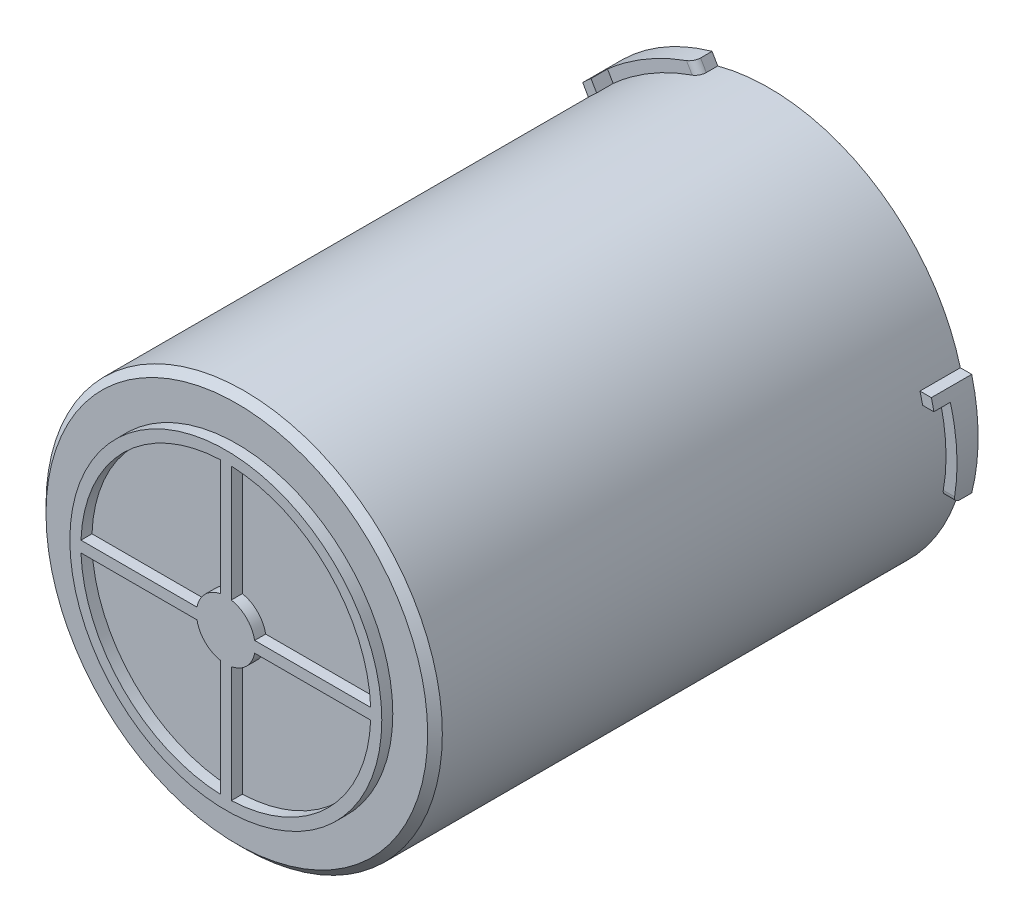
SolidWorks part; units mm, degrees
ref_plane "Спереди" through (0, 0, 0) normal (0, 0, 1) x (1, 0, 0)
ref_plane "Сверху" through (0, 0, 0) normal (0, 1, 0) x (1, 0, 0)
ref_plane "Справа" through (0, 0, 0) normal (1, 0, 0) x (0, 0, -1)
other "Configuration Table"
sketch "Эскиз1" plane through (0, 0, 0) normal (0, 1, 0) x (1, 0, 0)
  line L6 (0, 0) -> (-54, 0)
  line L7 (-54, 0) -> (-54, 145)
  line L8 (-54, 145) -> (-51, 145)
  line L9 (-51, 145) -> (-51, 3)
  line L10 (-51, 3) -> (0, 3)
  line L11 (0, 3) -> (0, 0)
  dimension "D1" = 3
  dimension "D2" = 3
  dimension "D3" = 145
  dimension "D4" = 54
revolve "Повернуть1" add sketch "Эскиз1" angle 360 about L11
ref_plane "Плоскость2" through (57, 0, 0) normal (1, 0, 0) x (0, 0, -1)
sketch "Эскиз2" plane through (57, 0, 0) normal (1, 0, 0) x (0, 0, -1)
  line L0 (145, 14) -> (145, -14)
  line L1 (145, -54) -> (145, 54) construction
  line L2 (145, -14) -> (140, -14)
  line L3 (140, -14) -> (138.5, 11)
  line L4 (138.5, 11) -> (134, 11)
  line L5 (134, 11) -> (134, 14)
  line L6 (134, 14) -> (145, 14)
  point P8 (0, 0)
  dimension "D1" = 28
  dimension "D2" = 3
  dimension "D3" = 6.5
  dimension "D4" = 11
  dimension "D5" = 5
  dimension "D6" = 14
extrude "Бобышка-Вытянуть1" add sketch "Эскиз2" against normal blind 10
fillet "Скругление1" radius 2 1 edges at (54.5768, -14, -140)
pattern_circular "Круговой массив2" count 3 over 360 about axis through (0, 0, 0) along (0, 0, 1) of "Бобышка-Вытянуть1", "Скругление1"
sketch "Эскиз3" plane through (0, 0, -145) normal (0, 0, -1) x (-1, 0, 0)
  circle A0 centre (0, 0) radius 51
extrude "Вырез-Вытянуть1" cut sketch "Эскиз3" against normal blind 15
sketch "Эскиз4" plane through (0, 0, -145) normal (0, 0, -1) x (-1, 0, 0)
  circle A0 centre (0, 0) radius 57
  circle A1 centre (0, 0) radius 62.6187
extrude "Вырез-Вытянуть2" cut sketch "Эскиз4" against normal blind 15
chamfer "Фаска1" distance 2 angle 45 1 edges at (-54, 0, 0)
sketch "Эскиз5" plane through (0, 0, 0) normal (0, 0, 1) x (1, 0, 0)
  circle A0 centre (0, 0) radius 42.5
  dimension "D1" = 85
fillet "Скругление2" radius 5 1 edges at (-51, 0, -3)
extrude "Бобышка-Вытянуть2" add sketch "Эскиз5" along normal blind 3
sketch "Эскиз7" plane through (0, 0, 3) normal (0, 0, 1) x (1, 0, 0)
  circle A0 centre (0, 0) radius 39.5
  dimension "D1" = 79
extrude "Вырез-Вытянуть3" cut sketch "Эскиз7" against normal up to surface (3 mm away) up to face at (42.5, 0, 0)
sketch "Эскиз8" plane through (0, 0, 0) normal (0, 0, 1) x (1, 0, 0)
  line L0 (-1.5, -41) -> (-1.5, 41)
  line L1 (-1.5, -41) -> (1.5, -41)
  line L2 (-1.5, 41) -> (1.5, 41)
  line L3 (1.5, -41) -> (1.5, 41)
  line L4 (-1.5, -41) -> (1.5, 41) construction
  line L5 (-1.5, 41) -> (1.5, -41) construction
  line L6 (-41, -1.5) -> (41, -1.5)
  line L7 (-41, -1.5) -> (-41, 1.5)
  line L8 (41, -1.5) -> (41, 1.5)
  line L9 (-41, 1.5) -> (41, 1.5)
  line L10 (-41, -1.5) -> (41, 1.5) construction
  line L11 (41, -1.5) -> (-41, 1.5) construction
  circle A0 centre (0, 0) radius 8
  circle M1 centre (0, 0) radius 39.5
  dimension "D1" = 16
  dimension "D2" = 3
  dimension "D3" = 82
  dimension "D4" = 82
  dimension "D5" = 3
extrude "Бобышка-Вытянуть4" add sketch "Эскиз8" along normal blind 3 contours A0 L3 L0 M1 | L3 A0 L0 L9 | L9 A0 L3 | L6 A0 L9 L3 | A0 L6 L9 M1 | L3 A0 L6 | L0 A0 L3 L6 | L9 L0 L6 L3 | L0 A0 L9 | L9 A0 L6 L0 | A0 L9 L6 M1 | L6 A0 L0 | A0 L0 L3 M1
equation "\"d\"=3"
equation "\"D1@Эскиз1\"=\"d\""
equation "\"D2@Эскиз1\"=\"d\""
